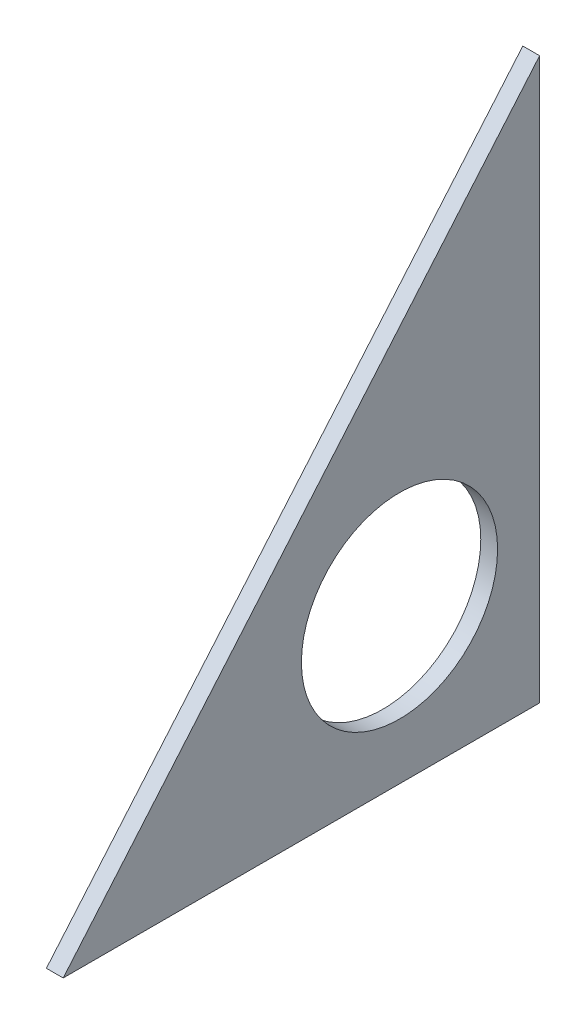
SolidWorks part; units mm, degrees
ref_plane "Front Plane" through (0, 0, 0) normal (0, 0, 1) x (1, 0, 0)
ref_plane "Top Plane" through (0, 0, 0) normal (0, 1, 0) x (1, 0, 0)
ref_plane "Right Plane" through (0, 0, 0) normal (1, 0, 0) x (0, 0, -1)
sketch "Sketch1" plane through (0, 0, 0) normal (1, 0, 0) x (0, 0, -1)
  line L0 (0, 0) -> (170, 0)
  line L1 (170, 0) -> (170, 200)
  line L2 (170, 200) -> (0, 0)
  circle A0 centre (120, 55) radius 35
  dimension "D3" = 70
  dimension "D1" = 170
  dimension "D2" = 200
  dimension "D4" = 55
  dimension "D5" = 50
extrude "Boss-Extrude1" add sketch "Sketch1" along normal blind 6
